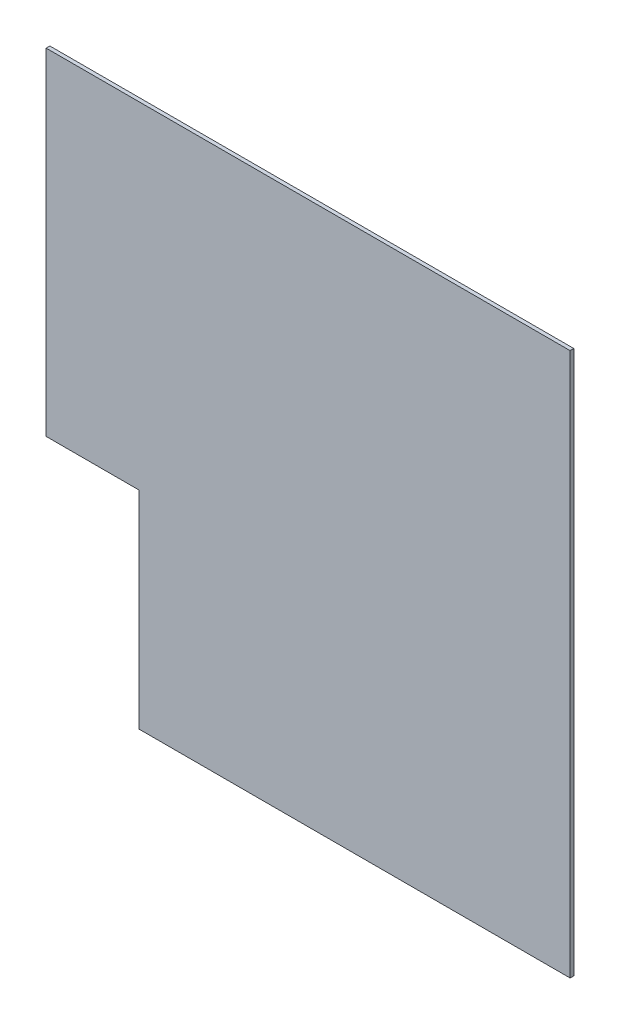
SolidWorks part; units mm, degrees
ref_plane "Plan de face" through (0, 0, 0) normal (0, 0, 1) x (1, 0, 0)
ref_plane "Plan de dessus" through (0, 0, 0) normal (0, 1, 0) x (1, 0, 0)
ref_plane "Plan de droite" through (0, 0, 0) normal (1, 0, 0) x (0, 0, -1)
sketch "Esquisse1" plane through (0, 0, 0) normal (0, 0, 1) x (1, 0, 0)
  line L0 (-405.4592, -167.491) -> (-243.4592, -167.491)
  line L1 (-243.4592, -529.491) -> (510.5408, -529.491)
  line L2 (-405.4592, -167.491) -> (-405.4592, 420.509)
  line L3 (-405.4592, 420.509) -> (510.5408, 420.509)
  line L4 (510.5408, -529.491) -> (510.5408, 420.509)
  line L5 (-391.2419, -322.248) -> (510.5408, 420.509) construction
  line L6 (-405.4592, 420.509) -> (510.5408, -529.491) construction
  line L7 (-243.4592, -167.491) -> (-243.4592, -529.491)
  point P0 (0, 0)
  dimension "D1" = 950
  dimension "D2" = 588
  dimension "D3" = 162
  dimension "D4" = 916
extrude "Boss.-Extru.1" add sketch "Esquisse1" along normal blind 6.5
